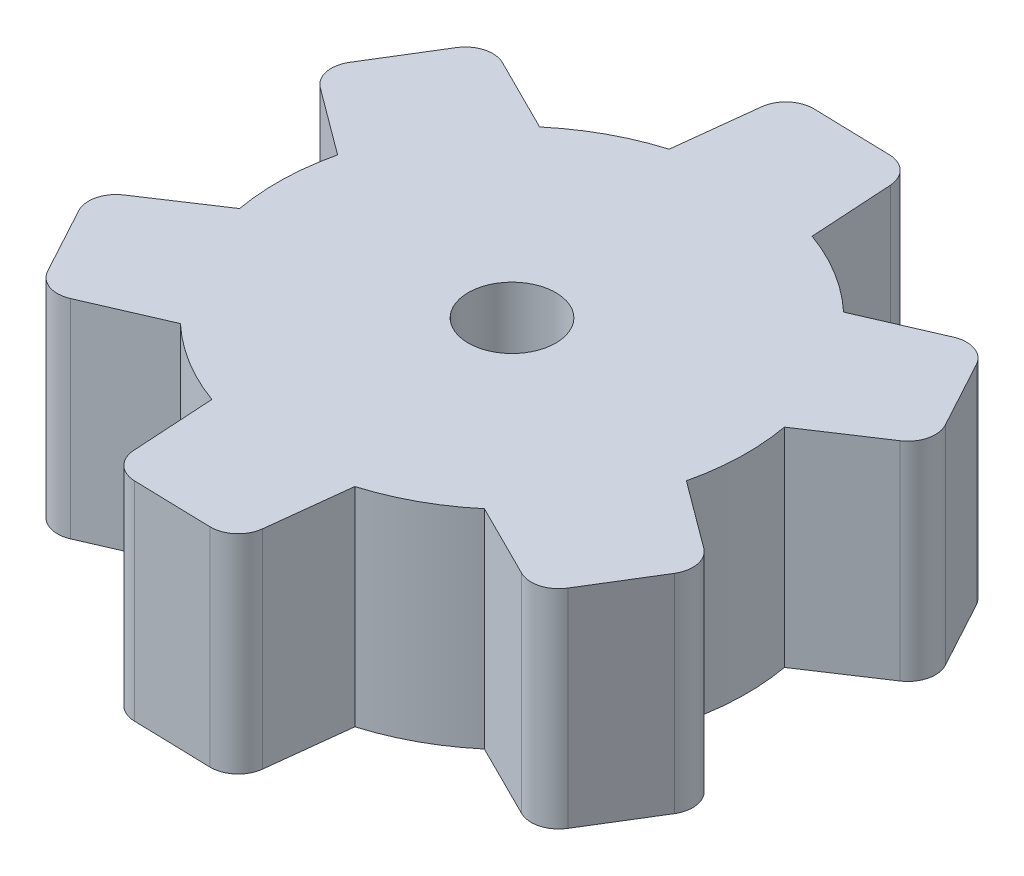
SolidWorks part; units mm, degrees
ref_plane "Front Plane" through (0, 0, 0) normal (0, 0, 1) x (1, 0, 0)
ref_plane "Top Plane" through (0, 0, 0) normal (0, 1, 0) x (1, 0, 0)
ref_plane "Right Plane" through (0, 0, 0) normal (1, 0, 0) x (0, 0, -1)
sketch "Sketch1" plane through (0, 0, 0) normal (0, 1, 0) x (1, 0, 0)
  circle A0 centre (0, 0) radius 8.509
  dimension "D1" = 17.018
extrude "Boss-Extrude1" add sketch "Sketch1" along normal blind 7.55
sketch "Sketch2" plane through (0, 7.55, 0) normal (0, 1, 0) x (1, 0, 0)
  circle A0 centre (0, 0) radius 1.5875
  dimension "D1" = 3.175
extrude "Cut-Extrude1" cut sketch "Sketch2" against normal through all
sketch "Sketch3" plane through (0, 7.55, 0) normal (0, 1, 0) x (1, 0, 0)
  line L0 (0, 0) -> (0.3304, 12.3503) construction
  line L1 (-1.0829, 12.0423) -> (1.7251, 11.9672)
  line L2 (-3.5854, 8.6079) -> (4.8903, 8.3812) construction
  line L3 (-2.1031, 11.1564) -> (-2.4474, 8.1494)
  line L4 (2.6965, 11.028) -> (2.8796, 8.0069)
  circle A0 centre (0, 0) radius 8.509 construction
  arc A1 (-2.1031, 11.1564) -> (-1.0829, 12.0423) centre (-1.1096, 11.0426) cw
  arc A2 (2.6965, 11.028) -> (1.7251, 11.9672) centre (1.6984, 10.9675) ccw
  arc A3 (2.8796, 8.0069) -> (-2.4474, 8.1494) centre (0, 0) ccw
  point P12 (-1.9989, 12.0668)
  point P17 (0.3211, 12.0047)
  dimension "D4" = 1
  dimension "D1" = 3.5
  dimension "D2" = 2.32
  dimension "D3" = 95
extrude "Boss-Extrude2" add sketch "Sketch3" against normal through all
pattern_circular "CirPattern1" count 6 over 360 about axis through (0, 0, 0) along (0, 1, 0) of "Boss-Extrude2"
